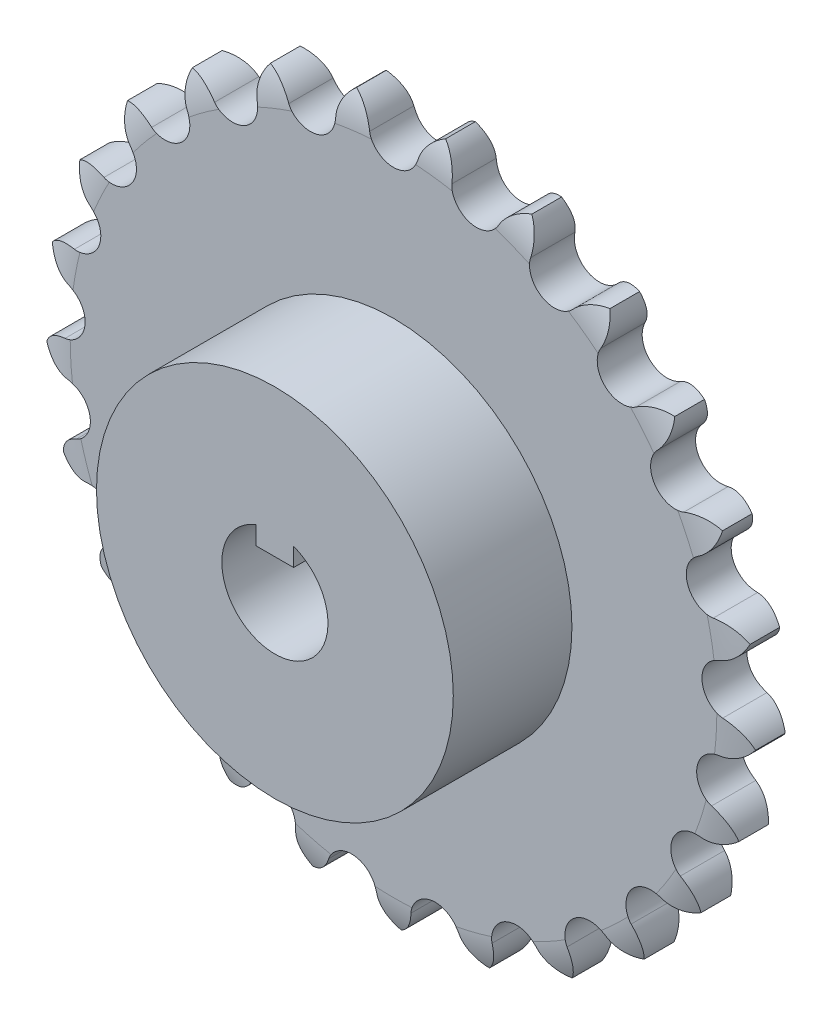
SolidWorks part; units mm, degrees
material "Acero aleado fundido"
ref_plane "Alzado" through (0, 0, 0) normal (0, 0, 1) x (1, 0, 0)
ref_plane "Planta" through (0, 0, 0) normal (0, 1, 0) x (1, 0, 0)
ref_plane "Vista lateral" through (0, 0, 0) normal (1, 0, 0) x (0, 0, -1)
sketch "Croquis1" plane through (0, 0, 0) normal (0, 0, 1) x (1, 0, 0)
  line L0 (0, 0) -> (0, 57) construction
  circle A0 centre (0, 0) radius 57 construction
  circle A1 centre (0, 0) radius 53.5 construction
  circle A2 centre (0, 0) radius 52 construction
  arc A5 (-3.8808, 52.5307) -> (3.8808, 52.5307) centre (0, 53.5) ccw
  arc A6 (7.3536, 56.5237) -> (3.8808, 52.5307) centre (9.537, 51.118) ccw
  arc A7 (15.1992, 49.7291) -> (15.3656, 51.246) centre (9.537, 51.118) ccw
  arc A8 (-7.3536, 56.5237) -> (-3.8808, 52.5307) centre (-9.537, 51.118) cw
  arc A9 (6.9343, 56.5766) -> (9.305, 51.8455) centre (3.4751, 51.8838) cw
  arc A10 (9.305, 51.8455) -> (16.8227, 49.9152) centre (13.3049, 51.8192) ccw
  arc A11 (21.1795, 52.9191) -> (16.8227, 49.9152) centre (21.9499, 47.1402) ccw
  arc A12 (20.7865, 53.0747) -> (21.9061, 47.9026) centre (16.2689, 49.3895) cw
  arc A13 (21.9061, 47.9026) -> (28.7076, 44.1634) centre (25.7738, 46.8824) ccw
  arc A14 (33.6745, 45.9894) -> (28.7076, 44.1634) centre (32.9836, 40.2005) ccw
  arc A15 (33.3325, 46.2379) -> (33.1308, 40.9498) centre (28.0405, 43.7919) cw
  arc A16 (33.1308, 40.9498) -> (38.7887, 35.6367) centre (36.6233, 38.9998) ccw
  arc A17 (44.0537, 36.1701) -> (38.7887, 35.6367) centre (41.9448, 30.7348) ccw
  arc A18 (43.7842, 36.4958) -> (42.2737, 31.424) centre (38.0501, 35.4427) cw
  arc A19 (42.2737, 31.424) -> (46.4326, 24.8707) centre (45.1715, 28.6667) ccw
  arc A20 (51.6648, 24.078) -> (46.4326, 24.8707) centre (48.2705, 19.338) ccw
  arc A21 (51.4848, 24.4605) -> (48.7604, 19.9237) centre (45.669, 24.8666) cw
  arc A22 (48.7604, 19.9237) -> (51.1589, 12.542) centre (50.8815, 16.5324) ccw
  arc A23 (56.0296, 10.4731) -> (51.1589, 12.542) centre (51.5632, 6.7261) ccw
  arc A24 (55.9504, 10.8883) -> (52.1834, 7.1716) centre (50.4183, 12.7279) cw
  arc A25 (52.1834, 7.1716) -> (52.6707, -0.5747) centre (53.3944, 3.3593) ccw
  arc A26 (56.8739, -3.79) -> (52.6707, -0.5747) centre (51.6159, -6.3085) ccw
  arc A27 (56.9004, -3.3681) -> (52.3274, -6.0312) centre (51.9996, -0.2105) cw
  arc A28 (52.3274, -6.0312) -> (50.8731, -13.6553) centre (52.5524, -10.0249) ccw
  arc A29 (54.1445, -17.8148) -> (50.8731, -13.6553) centre (48.4255, -18.9466) ccw
  arc A30 (54.2752, -17.4128) -> (49.1836, -18.855) centre (50.3136, -13.1356) cw
  arc A31 (49.1836, -18.855) -> (45.8788, -25.8779) centre (48.4082, -22.7792) ccw
  arc A32 (48.0131, -30.7204) -> (45.8788, -25.8779) centre (42.1922, -30.3943) ccw
  arc A33 (48.2396, -30.3635) -> (42.9493, -30.4941) centre (45.4662, -25.2354) cw
  arc A34 (42.9493, -30.4941) -> (38.0019, -36.4745) centre (41.2225, -34.1022) ccw
  arc A35 (38.8649, -41.6956) -> (38.0019, -36.4745) centre (33.3079, -39.9322) ccw
  arc A36 (39.173, -41.4063) -> (34.0164, -40.2172) centre (37.762, -35.7496) cw
  arc A37 (34.0164, -40.2172) -> (27.7372, -44.7793) centre (31.4465, -43.2824) ccw
  arc A38 (27.2746, -50.051) -> (27.7372, -44.7793) centre (22.3308, -46.961) ccw
  arc A39 (27.645, -49.8473) -> (22.9461, -47.4132) centre (27.6851, -44.0175) cw
  arc A40 (22.9461, -47.4132) -> (15.7296, -50.2704) centre (19.6947, -49.743) ccw
  arc A41 (13.9705, -55.2614) -> (15.7296, -50.2704) centre (9.9505, -51.0391) ccw
  arc A42 (14.3799, -55.1563) -> (10.434, -51.6301) centre (15.8686, -49.5196) cw
  arc A43 (10.434, -51.6301) -> (2.7337, -52.6029) centre (6.7053, -53.0781) ccw
  arc A44 (-0.2113, -56.9996) -> (2.7337, -52.6029) centre (-3.055, -51.9102) ccw
  arc A45 (0.2113, -56.9996) -> (-2.7337, -52.6029) centre (3.055, -51.9102) cw
  arc A46 (-2.7337, -52.6029) -> (-10.434, -51.6301) centre (-6.7053, -53.0781) ccw
  arc A47 (-14.3799, -55.1563) -> (-10.434, -51.6301) centre (-15.8686, -49.5196) ccw
  arc A48 (-13.9705, -55.2614) -> (-15.7296, -50.2704) centre (-9.9505, -51.0391) cw
  arc A49 (-15.7296, -50.2704) -> (-22.9461, -47.4132) centre (-19.6947, -49.743) ccw
  arc A50 (-27.645, -49.8473) -> (-22.9461, -47.4132) centre (-27.6851, -44.0175) ccw
  arc A51 (-27.2746, -50.051) -> (-27.7372, -44.7793) centre (-22.3308, -46.961) cw
  arc A52 (-27.7372, -44.7793) -> (-34.0164, -40.2172) centre (-31.4465, -43.2824) ccw
  arc A53 (-39.173, -41.4063) -> (-34.0164, -40.2172) centre (-37.762, -35.7496) ccw
  arc A54 (-38.8649, -41.6956) -> (-38.0019, -36.4745) centre (-33.3079, -39.9322) cw
  arc A55 (-38.0019, -36.4745) -> (-42.9493, -30.4941) centre (-41.2225, -34.1022) ccw
  arc A56 (-48.2396, -30.3635) -> (-42.9493, -30.4941) centre (-45.4662, -25.2354) ccw
  arc A57 (-48.0131, -30.7204) -> (-45.8788, -25.8779) centre (-42.1922, -30.3943) cw
  arc A58 (-45.8788, -25.8779) -> (-49.1836, -18.855) centre (-48.4082, -22.7792) ccw
  arc A59 (-54.2752, -17.4128) -> (-49.1836, -18.855) centre (-50.3136, -13.1356) ccw
  arc A60 (-54.1445, -17.8148) -> (-50.8731, -13.6553) centre (-48.4255, -18.9466) cw
  arc A61 (-50.8731, -13.6553) -> (-52.3274, -6.0312) centre (-52.5524, -10.0249) ccw
  arc A62 (-56.9004, -3.3681) -> (-52.3274, -6.0312) centre (-51.9996, -0.2105) ccw
  arc A63 (-56.8739, -3.79) -> (-52.6707, -0.5747) centre (-51.6159, -6.3085) cw
  arc A64 (-52.6707, -0.5747) -> (-52.1834, 7.1716) centre (-53.3944, 3.3593) ccw
  arc A65 (-55.9504, 10.8883) -> (-52.1834, 7.1716) centre (-50.4183, 12.7279) ccw
  arc A66 (-56.0296, 10.4731) -> (-51.1589, 12.542) centre (-51.5632, 6.7261) cw
  arc A67 (-51.1589, 12.542) -> (-48.7604, 19.9237) centre (-50.8815, 16.5324) ccw
  arc A68 (-51.4848, 24.4605) -> (-48.7604, 19.9237) centre (-45.669, 24.8666) ccw
  arc A69 (-51.6648, 24.078) -> (-46.4326, 24.8707) centre (-48.2705, 19.338) cw
  arc A70 (-46.4326, 24.8707) -> (-42.2737, 31.424) centre (-45.1715, 28.6667) ccw
  arc A71 (-43.7842, 36.4958) -> (-42.2737, 31.424) centre (-38.0501, 35.4427) ccw
  arc A72 (-44.0537, 36.1701) -> (-38.7887, 35.6367) centre (-41.9448, 30.7348) cw
  arc A73 (-38.7887, 35.6367) -> (-33.1308, 40.9498) centre (-36.6233, 38.9998) ccw
  arc A74 (-33.3325, 46.2379) -> (-33.1308, 40.9498) centre (-28.0405, 43.7919) ccw
  arc A75 (-33.6745, 45.9894) -> (-28.7076, 44.1634) centre (-32.9836, 40.2005) cw
  arc A76 (-28.7076, 44.1634) -> (-21.9061, 47.9026) centre (-25.7738, 46.8824) ccw
  arc A77 (-20.7865, 53.0747) -> (-21.9061, 47.9026) centre (-16.2689, 49.3895) ccw
  arc A78 (-21.1795, 52.9191) -> (-16.8227, 49.9152) centre (-21.9499, 47.1402) cw
  arc A79 (-16.8227, 49.9152) -> (-9.305, 51.8455) centre (-13.3049, 51.8192) ccw
  arc A80 (-6.9343, 56.5766) -> (-9.305, 51.8455) centre (-3.4751, 51.8838) ccw
  circle A81 centre (0, 0) radius 19
  point P186 (0, 0)
  dimension "D1" = 114
  dimension "D2" = 107
  dimension "D3" = 104
  dimension "D4" = 8
  dimension "D5" = 11.66
  dimension "D7" = 38
  dimension "D6" = 25
extrude "Saliente-Extruir1" add sketch "Croquis1" along normal mid plane 7.2 contours A8 A80 A79 A78 A77 A76 A75 A74 A73 A72 A71 A70 A69 A68 A67 A66 A65 A64 A63 A62 A61 A60 A59 A58 A57 A56 A55 A54 A53 A52 A51 A50 A49 A48 A47 A46 A45 A44 A43 A42 A41 A40 A39 A38 A37 A36 A35 A34 A33 A32 A31
sketch "Croquis2" plane through (0, 0, 3.6) normal (0, 0, 1) x (1, 0, 0)
  circle A0 centre (0, 0) radius 28.575
  circle A1 centre (0, 0) radius 19 construction
  circle A2 centre (0, 0) radius 19
  dimension "D1" = 57.15
extrude "Saliente-Extruir2" add sketch "Croquis2" along normal blind 19
sketch "Croquis3" plane through (0, 0, 22.6) normal (0, 0, 1) x (1, 0, 0)
  line L0 (0, 0) -> (0, 19) construction
  line L2 (-4.75, 21.4) -> (4.75, 21.4)
  line L3 (-4.75, 21.4) -> (-4.75, 16.6)
  line L4 (-4.75, 16.6) -> (4.75, 16.6)
  line L5 (4.75, 21.4) -> (4.75, 16.6)
  line L6 (-4.75, 21.4) -> (4.75, 16.6) construction
  line L7 (-4.75, 16.6) -> (4.75, 21.4) construction
  circle A1 centre (0, 0) radius 19 construction
  dimension "D1" = 9.5
  dimension "D2" = 4.8
extrude "Cortar-Extruir1" cut sketch "Croquis3" against normal through all
sketch "Croquis4" plane through (0, 0, 0) normal (1, 0, 0) x (0, 0, -1)
  line L0 (0, 56.4271) -> (0, 47.0486) construction
  line L1 (-3.6, 56.4271) -> (3.6, 56.4271) construction
  line L2 (-2.1, 58.8113) -> (-2.1, 48.3808) construction
  line L3 (-3.6, 56.4271) -> (-3.6, 51.8455) construction
  line L4 (-2.1, 57.4271) -> (-9.3502, 57.4271)
  line L5 (-9.3502, 57.4271) -> (-9.3502, 51.0771)
  line L6 (-9.3502, 51.0771) -> (-3.6, 51.0771)
  line L7 (-3.6, 52.8816) -> (-3.6, 47.9026) construction
  line L8 (9.3502, 51.0771) -> (3.6, 51.0771)
  line L9 (9.3502, 57.4271) -> (9.3502, 51.0771)
  line L10 (2.1, 57.4271) -> (9.3502, 57.4271)
  arc A0 (-2.1, 57.4271) -> (-3.6, 51.0771) centre (9.0951, 51.4305) ccw
  arc A1 (2.1, 57.4271) -> (3.6, 51.0771) centre (-9.0951, 51.4305) cw
  dimension "D2" = 12.7
  dimension "D1" = 1.5
  dimension "D3" = 1
  dimension "D4" = 6.35
ref_axis "Eje1" through (0, 0, 81.5759) along (0, 0, -1)
revolve "Cortar-Revolución1" cut sketch "Croquis4" angle 360 about axis through (0, 0, 81.5759) along (0, 0, -1)
sketch "Croquis5" plane through (0, 0, 22.6) normal (0, 0, 1) x (1, 0, 0)
  line L0 (-4.75, 18.3967) -> (-4.75, 21.4)
  line L1 (-4.75, 21.4) -> (4.75, 21.4)
  line L2 (4.75, 21.4) -> (4.75, 18.3967)
  line L3 (4.75, 18.3967) -> (4.75, 21.4) construction
  arc A0 (-4.75, 18.3967) -> (4.75, 18.3967) centre (0, 0) ccw
extrude "Saliente-Extruir4" add sketch "Croquis5" against normal blind 70.2 and the other way blind 4
sketch "Croquis6" plane through (0, 0, -47.6) normal (0, 0, -1) x (-1, 0, 0)
  line L0 (-3, 5.003) -> (-3, 7.953)
  line L1 (-3, 5.003) -> (3, 5.003)
  line L2 (3, 5.003) -> (3, 7.953)
  arc A0 (-3, 7.953) -> (3, 7.953) centre (0, 0) ccw
  circle A1 centre (0, 0) radius 10.5
  dimension "D1" = 17
  dimension "D2" = 21
  dimension "D3" = 6
  dimension "D4" = 2.95
  dimension "D5" = 2.95
extrude "Cortar-Extruir2" cut sketch "Croquis6" against normal blind 128 contours A0 L2 L1 L0
sketch "Croquis8" plane through (0, 0, -47.6) normal (0, 0, -1) x (-1, 0, 0)
  line L0 (-3, 5.003) -> (3, 5.003)
  line L1 (3, 5.003) -> (3, 7.953)
  line L2 (-3, 5.003) -> (-3, 7.953)
  line L3 (-4.75, 18.3967) -> (-4.75, 21.4)
  line L4 (-4.75, 21.4) -> (4.75, 21.4)
  line L5 (4.75, 21.4) -> (4.75, 18.3967)
  arc A0 (-3, 7.953) -> (3, 7.953) centre (0, 0) ccw
  arc A1 (-4.75, 18.3967) -> (4.75, 18.3967) centre (0, 0) ccw
extrude "Cortar-Extruir3" cut sketch "Croquis8" against normal blind 44 contours A1 L5 L4 L3
sketch "Croquis9" plane through (0, 0, 26.6) normal (0, 0, 1) x (1, 0, 0)
  circle A1 centre (0, 0) radius 28.4343
extrude "Cortar-Extruir4" cut sketch "Croquis9" against normal blind 4
